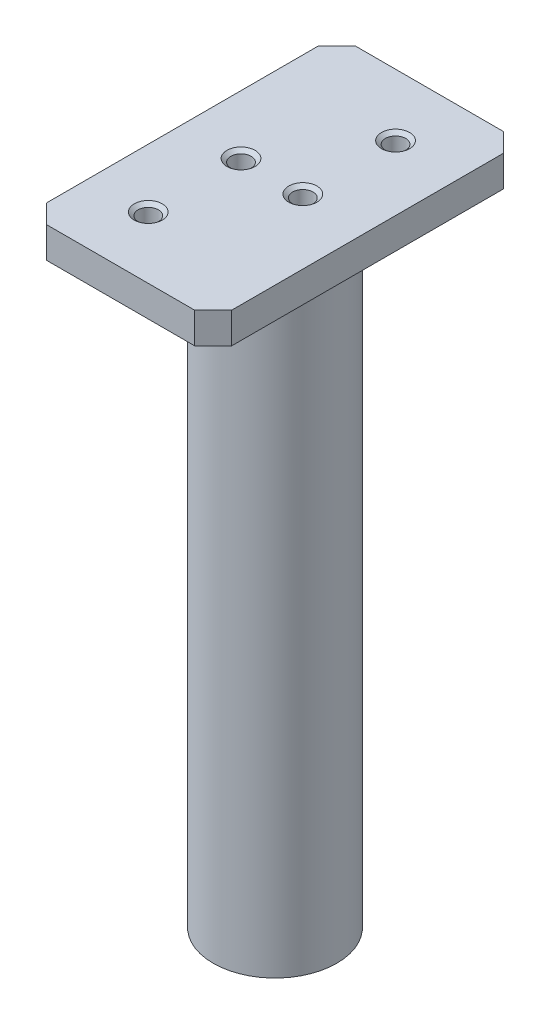
SolidWorks part; units mm, degrees
material "Alloy Steel"
ref_plane "Front Plane" through (0, 0, 0) normal (0, 0, 1) x (1, 0, 0)
ref_plane "Top Plane" through (0, 0, 0) normal (0, 1, 0) x (1, 0, 0)
ref_plane "Right Plane" through (0, 0, 0) normal (1, 0, 0) x (0, 0, -1)
sketch "Sketch1" plane through (0, 0, 0) normal (0, 1, 0) x (1, 0, 0)
  line L1 (-15, 25) -> (15, 25)
  line L2 (-15, 25) -> (-15, -25)
  line L3 (-15, -25) -> (15, -25)
  line L4 (15, 25) -> (15, -25)
  point P0 (0, 0)
  dimension "D1" = 50
  dimension "D2" = 30
extrude "Boss-Extrude1" add sketch "Sketch1" along normal blind 5
hole_wizard "M4x0.7 Tapped Hole1" positions "Sketch2" profile "Sketch3" tap size "M4x0.7" standard "JIS" end condition up to next
sketch "Sketch2" plane through (0, 5, 0) normal (0, 1, 0) x (1, 0, 0)
  line L0 (0, 25) -> (0, -25) construction
  line L1 (15, 25) -> (-15, 25) construction
  line L2 (-15, -25) -> (15, -25) construction
  point P0 (-5.5, -15)
  point P2 (-5.5, 0)
  point P4 (4.5, 0)
  point P6 (4.5, 15)
  dimension "D1" = 5.5
  dimension "D2" = 15
  dimension "D3" = 10
  dimension "D4" = 4.5
  dimension "D5" = 15
  dimension "D6" = 10
sketch "Sketch3" plane through (-5.5, 5, 15) normal (1, 0, 0) x (0, 0, 1)
  line L0 (0, 0) -> (0, 5)
  line L1 (0, 5) -> (1.65, 5)
  line L2 (1.65, 5) -> (1.65, 0.5244)
  line L3 (1.65, 0.5244) -> (2.275, 0)
  line L5 (2.275, 0) -> (0, 0)
  line L6 (-1.65, 0.5244) -> (-2.275, 0) construction
  line L11 (0, -6.35) -> (0, 107.95) construction
  dimension "Thru Tap Drill Dia." = 3.3
  dimension "Thru Tap Drill Depth" = 5
  dimension "Near C'Sink Dia." = 4.55
  dimension "Near C'Sink Angle" = 100
cosmetic thread "Hole Thread1" parameters "D2"=4
cosmetic thread "Hole Thread2" parameters "D2"=4
cosmetic thread "Hole Thread3" parameters "D2"=4
cosmetic thread "Hole Thread4" parameters "D2"=4
sketch "Sketch4" plane through (0, 0, 0) normal (0, -1, 0) x (1, 0, 0)
  line L0 (-15.3784, 0) -> (15, 0) construction
  line L1 (15, 25) -> (15, -25) construction
  circle A0 centre (0, 0) radius 10
  dimension "D1" = 20
extrude "Boss-Extrude2" add sketch "Sketch4" along normal blind 100
chamfer "Chamfer1" distance 3 angle 45 4 edges at (-15, 2.5, 25) (-15, 2.5, -25) (15, 2.5, -25) (15, 2.5, 25)
